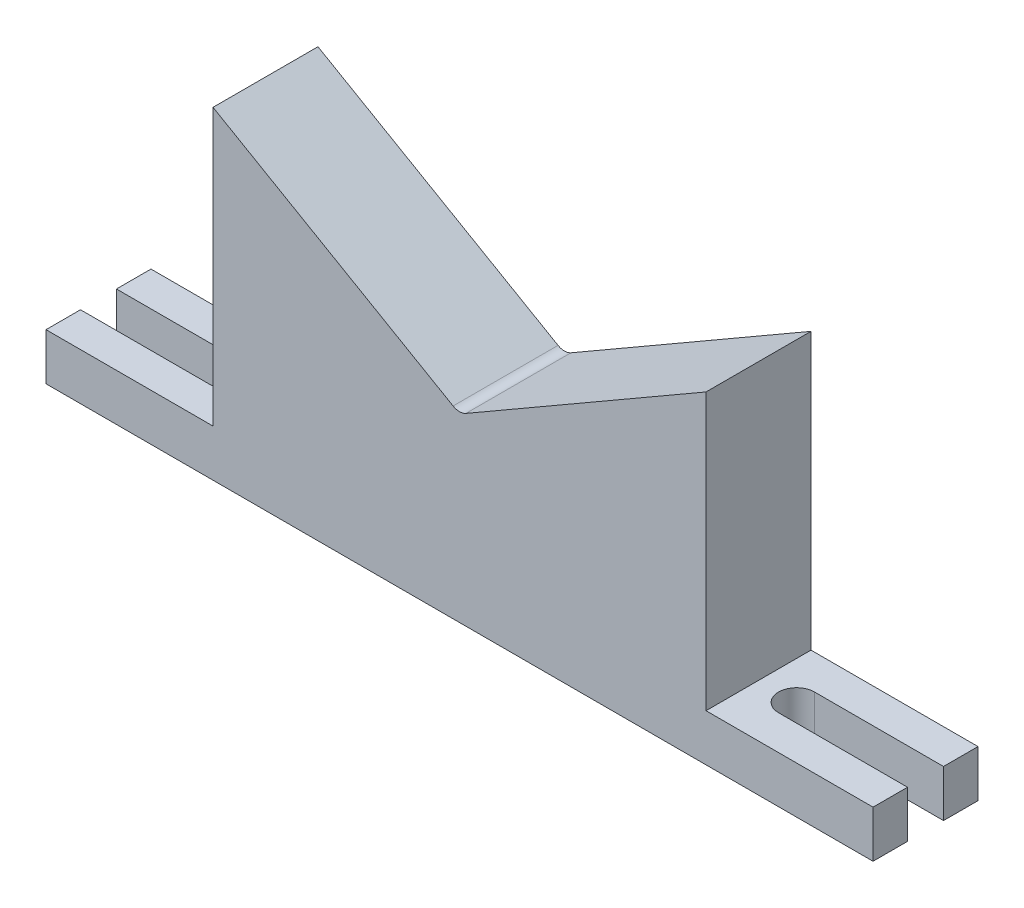
SolidWorks part; units mm, degrees
ref_plane "Front Plane" through (0, 0, 0) normal (0, 0, 1) x (1, 0, 0)
ref_plane "Top Plane" through (0, 0, 0) normal (0, 1, 0) x (1, 0, 0)
ref_plane "Right Plane" through (0, 0, 0) normal (1, 0, 0) x (0, 0, -1)
sketch "Sketch1" plane through (0, 0, 0) normal (0, 0, 1) x (1, 0, 0)
  line L0 (-48.735, 28.1372) -> (0, 0)
  line L3 (81.623, -35.7145) -> (-81.623, -35.7145)
  line L4 (-48.735, -26.4435) -> (-48.735, 28.1372)
  line L5 (0, 0) -> (0, -35.7145) construction
  line L6 (0, 0) -> (0, 44.7273) construction
  line L7 (81.623, -35.7145) -> (81.755, -35.7145)
  line L8 (-48.735, -26.4435) -> (-81.755, -26.4435)
  line L10 (-81.623, -35.7145) -> (-81.755, -35.7145)
  line L11 (-81.755, -26.4435) -> (-81.755, -35.7145)
  line L12 (81.755, -26.4435) -> (81.755, -35.7145)
  line L13 (48.735, -26.4435) -> (81.755, -26.4435)
  line L14 (-38.735, 44.7273) -> (-38.735, -35.7145) construction
  line L15 (48.735, 28.1372) -> (0, 0)
  line L16 (48.735, -26.4435) -> (48.735, 28.1372)
  circle A0 centre (0, 44.7273) radius 38.735 construction
  point P18 (-81.755, -31.079)
  dimension "D1" = 77.47
  dimension "D4" = 10
  dimension "D2" = 80.4418
  dimension "D3" = 9.271
  dimension "D5" = 33.02
  dimension "D6" = 120
extrude "Boss-Extrude1" add sketch "Sketch1" along normal blind 20.7518
sketch "Sketch2" plane through (0, -26.4435, 0) normal (0, 1, 0) x (1, 0, 0)
  line L0 (-107.2529, -10.3759) -> (-56.2571, -10.3759) construction
  line L1 (-107.2529, -6.8199) -> (-56.2571, -6.8199)
  line L2 (-107.2529, -13.9319) -> (-56.2571, -13.9319)
  line L3 (-81.755, -20.7518) -> (-81.755, 0) construction
  line L4 (-81.755, -6.8199) -> (-81.755, -13.9319)
  line L5 (-81.755, 0) -> (-81.755, -20.7518) construction
  line L6 (0, 0) -> (0, -20.7518) construction
  line L7 (0, -20.7518) -> (0, 0) construction
  line L8 (107.2529, -10.3759) -> (56.2571, -10.3759) construction
  line L9 (107.2529, -6.8199) -> (56.2571, -6.8199)
  line L10 (107.2529, -13.9319) -> (56.2571, -13.9319)
  line L11 (81.755, -6.8199) -> (81.755, -13.9319)
  arc A0 (-107.2529, -6.8199) -> (-107.2529, -13.9319) centre (-107.2529, -10.3759) ccw
  arc A1 (-56.2571, -13.9319) -> (-56.2571, -6.8199) centre (-56.2571, -10.3759) ccw
  arc A2 (107.2529, -6.8199) -> (107.2529, -13.9319) centre (107.2529, -10.3759) cw
  arc A3 (56.2571, -13.9319) -> (56.2571, -6.8199) centre (56.2571, -10.3759) cw
  point P2 (-81.755, -10.3759)
  point P22 (81.755, -10.3759)
  line M3 (-81.755, 0) -> (-81.755, -20.7518)
  dimension "D1" = 7.112
extrude "Cut-Extrude1" cut sketch "Sketch2" against normal blind 10 contours L2 A1 L1 M3 | A3 L10 L11 L9
fillet "Fillet1" radius 2.54 1 edges at (0, 0, 10.3759)
